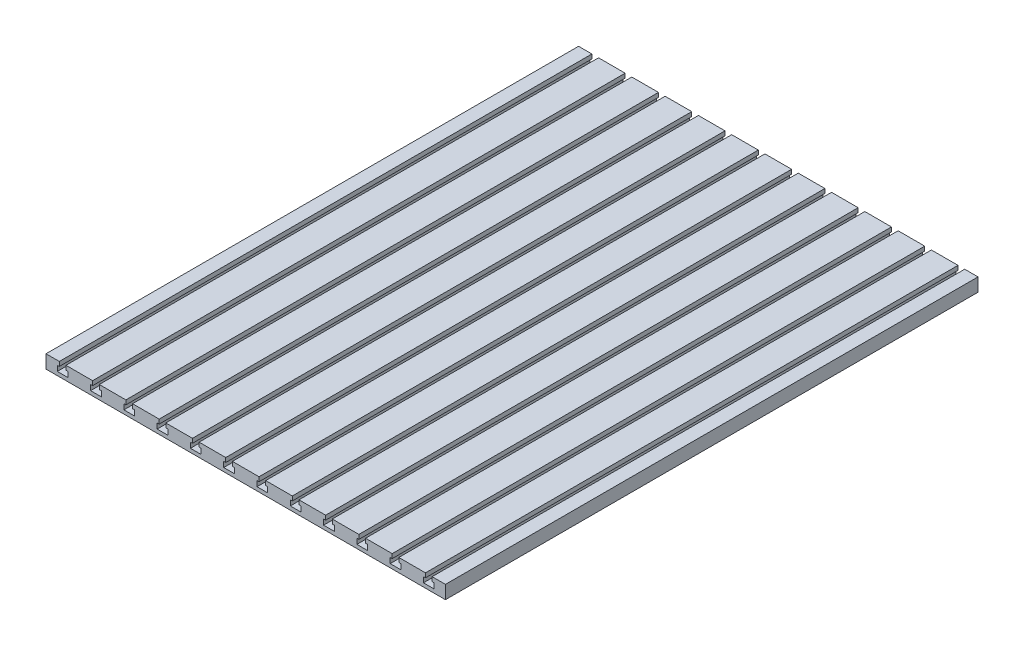
SolidWorks part; units mm, degrees
material "6063-T6"
ref_plane "Front Plane" through (0, 0, 0) normal (0, 0, 1) x (1, 0, 0)
ref_plane "Top Plane" through (0, 0, 0) normal (0, 1, 0) x (1, 0, 0)
ref_plane "Right Plane" through (0, 0, 0) normal (1, 0, 0) x (0, 0, -1)
sketch "Sketch1" plane through (0, 0, 0) normal (0, 0, 1) x (1, 0, 0)
  line L1 (0, 0) -> (-600, 0)
  line L2 (0, 0) -> (0, 20)
  line L3 (0, 20) -> (-600, 20)
  line L4 (-600, 0) -> (-600, 20)
  dimension "D1" = 600
  dimension "D2" = 20
extrude "Boss-Extrude1" add sketch "Sketch1" along normal blind 800
sketch "Sketch2" plane through (0, 0, 800) normal (0, 0, 1) x (1, 0, 0)
  line L0 (-580, 20) -> (-580, 13.5)
  line L1 (0, 20) -> (-600, 20) construction
  line L2 (-580, 13.5) -> (-583, 13.5)
  line L3 (-583, 13.5) -> (-583, 5.5)
  line L4 (-583, 5.5) -> (-567, 5.5)
  line L5 (-575, 5.5) -> (-575, 20) construction
  line L6 (-567, 13.5) -> (-567, 5.5)
  line L7 (-570, 13.5) -> (-567, 13.5)
  line L8 (-570, 20) -> (-570, 13.5)
  line L9 (-530, 20) -> (-530, 13.5)
  line L10 (-530, 13.5) -> (-533, 13.5)
  line L11 (-533, 13.5) -> (-533, 5.5)
  line L12 (-533, 5.5) -> (-517, 5.5)
  line L13 (-517, 13.5) -> (-517, 5.5)
  line L14 (-520, 13.5) -> (-517, 13.5)
  line L15 (-520, 20) -> (-520, 13.5)
  line L16 (-530, 20) -> (-520, 20)
  line L17 (-525, 5.5) -> (-525, 20) construction
  line L18 (-480, 20) -> (-480, 13.5)
  line L19 (-480, 13.5) -> (-483, 13.5)
  line L20 (-483, 13.5) -> (-483, 5.5)
  line L21 (-483, 5.5) -> (-467, 5.5)
  line L22 (-467, 13.5) -> (-467, 5.5)
  line L23 (-470, 13.5) -> (-467, 13.5)
  line L24 (-470, 20) -> (-470, 13.5)
  line L25 (-480, 20) -> (-470, 20)
  line L26 (-475, 5.5) -> (-475, 20) construction
  line L27 (-430, 20) -> (-430, 13.5)
  line L28 (-430, 13.5) -> (-433, 13.5)
  line L29 (-433, 13.5) -> (-433, 5.5)
  line L30 (-433, 5.5) -> (-417, 5.5)
  line L31 (-417, 13.5) -> (-417, 5.5)
  line L32 (-420, 13.5) -> (-417, 13.5)
  line L33 (-420, 20) -> (-420, 13.5)
  line L34 (-430, 20) -> (-420, 20)
  line L35 (-425, 5.5) -> (-425, 20) construction
  line L36 (-380, 20) -> (-380, 13.5)
  line L37 (-380, 13.5) -> (-383, 13.5)
  line L38 (-383, 13.5) -> (-383, 5.5)
  line L39 (-383, 5.5) -> (-367, 5.5)
  line L40 (-367, 13.5) -> (-367, 5.5)
  line L41 (-370, 13.5) -> (-367, 13.5)
  line L42 (-370, 20) -> (-370, 13.5)
  line L43 (-380, 20) -> (-370, 20)
  line L44 (-375, 5.5) -> (-375, 20) construction
  line L45 (-330, 20) -> (-330, 13.5)
  line L46 (-330, 13.5) -> (-333, 13.5)
  line L47 (-333, 13.5) -> (-333, 5.5)
  line L48 (-333, 5.5) -> (-317, 5.5)
  line L49 (-317, 13.5) -> (-317, 5.5)
  line L50 (-320, 13.5) -> (-317, 13.5)
  line L51 (-320, 20) -> (-320, 13.5)
  line L52 (-330, 20) -> (-320, 20)
  line L53 (-325, 5.5) -> (-325, 20) construction
  line L54 (-280, 20) -> (-280, 13.5)
  line L55 (-280, 13.5) -> (-283, 13.5)
  line L56 (-283, 13.5) -> (-283, 5.5)
  line L57 (-283, 5.5) -> (-267, 5.5)
  line L58 (-267, 13.5) -> (-267, 5.5)
  line L59 (-270, 13.5) -> (-267, 13.5)
  line L60 (-270, 20) -> (-270, 13.5)
  line L61 (-280, 20) -> (-270, 20)
  line L62 (-275, 5.5) -> (-275, 20) construction
  line L63 (-230, 20) -> (-230, 13.5)
  line L64 (-230, 13.5) -> (-233, 13.5)
  line L65 (-233, 13.5) -> (-233, 5.5)
  line L66 (-233, 5.5) -> (-217, 5.5)
  line L67 (-217, 13.5) -> (-217, 5.5)
  line L68 (-220, 13.5) -> (-217, 13.5)
  line L69 (-220, 20) -> (-220, 13.5)
  line L70 (-230, 20) -> (-220, 20)
  line L71 (-225, 5.5) -> (-225, 20) construction
  line L72 (-180, 20) -> (-180, 13.5)
  line L73 (-180, 13.5) -> (-183, 13.5)
  line L74 (-183, 13.5) -> (-183, 5.5)
  line L75 (-183, 5.5) -> (-167, 5.5)
  line L76 (-167, 13.5) -> (-167, 5.5)
  line L77 (-170, 13.5) -> (-167, 13.5)
  line L78 (-170, 20) -> (-170, 13.5)
  line L79 (-180, 20) -> (-170, 20)
  line L80 (-175, 5.5) -> (-175, 20) construction
  line L81 (-600, 20) -> (-600, 0) construction
  line L82 (-580, 20) -> (-570, 20)
  line L83 (-130, 20) -> (-130, 13.5)
  line L84 (-130, 13.5) -> (-133, 13.5)
  line L85 (-133, 13.5) -> (-133, 5.5)
  line L86 (-133, 5.5) -> (-117, 5.5)
  line L87 (-117, 13.5) -> (-117, 5.5)
  line L88 (-120, 13.5) -> (-117, 13.5)
  line L89 (-120, 20) -> (-120, 13.5)
  line L90 (-130, 20) -> (-120, 20)
  line L91 (-125, 5.5) -> (-125, 20) construction
  line L92 (-80, 20) -> (-80, 13.5)
  line L93 (-80, 13.5) -> (-83, 13.5)
  line L94 (-83, 13.5) -> (-83, 5.5)
  line L95 (-83, 5.5) -> (-67, 5.5)
  line L96 (-67, 13.5) -> (-67, 5.5)
  line L97 (-70, 13.5) -> (-67, 13.5)
  line L98 (-70, 20) -> (-70, 13.5)
  line L99 (-80, 20) -> (-70, 20)
  line L100 (-75, 5.5) -> (-75, 20) construction
  line L101 (-30, 20) -> (-30, 13.5)
  line L102 (-30, 13.5) -> (-33, 13.5)
  line L103 (-33, 13.5) -> (-33, 5.5)
  line L104 (-33, 5.5) -> (-17, 5.5)
  line L105 (-17, 13.5) -> (-17, 5.5)
  line L106 (-20, 13.5) -> (-17, 13.5)
  line L107 (-20, 20) -> (-20, 13.5)
  line L108 (-30, 20) -> (-20, 20)
  line L109 (-25, 5.5) -> (-25, 20) construction
  dimension "D1" = 5
  dimension "D2" = 6.5
  dimension "D3" = 8
  dimension "D4" = 8
  dimension "D6" = 25
  dimension "D5" = 12
extrude "Cut-Extrude1" cut sketch "Sketch2" against normal through all
